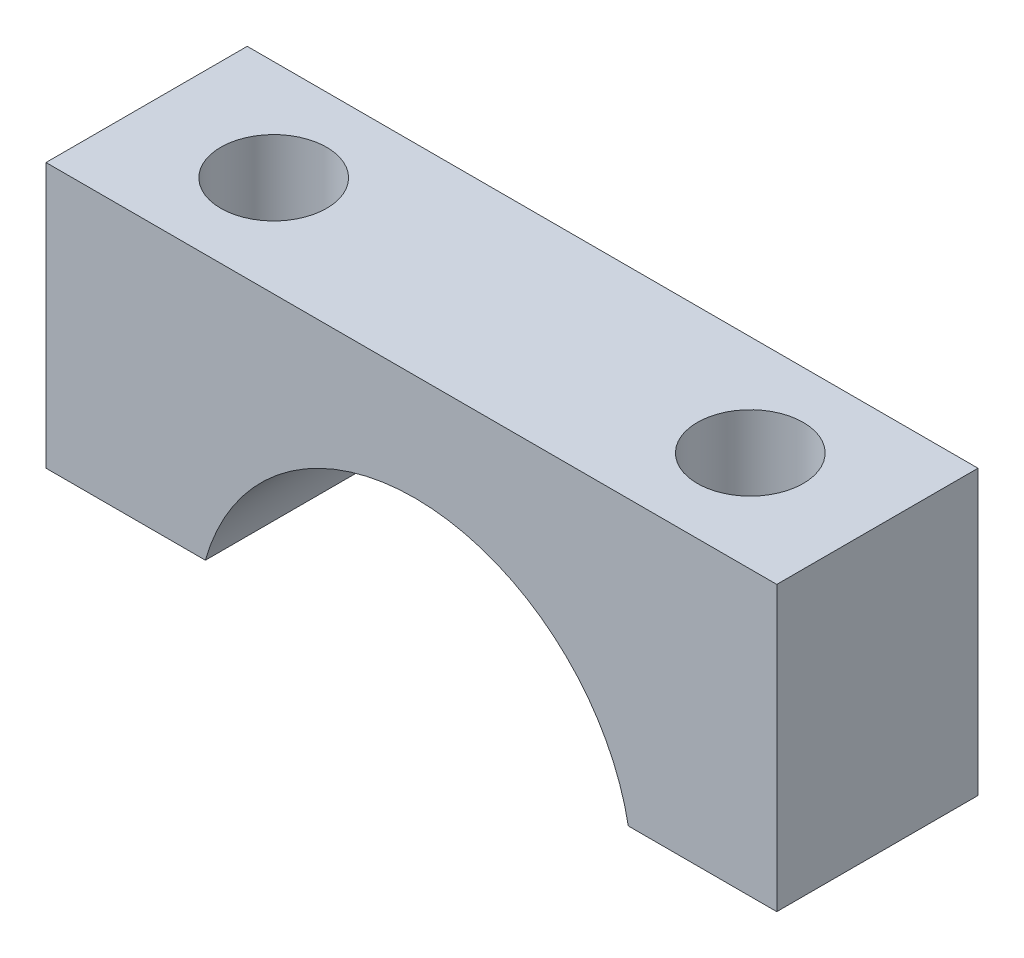
SolidWorks part; units mm, degrees
ref_plane "Front Plane" through (0, 0, 0) normal (0, 0, 1) x (1, 0, 0)
ref_plane "Top Plane" through (0, 0, 0) normal (0, 1, 0) x (1, 0, 0)
ref_plane "Right Plane" through (0, 0, 0) normal (1, 0, 0) x (0, 0, -1)
sketch "Sketch1" plane through (0, 0, 0) normal (0, 0, 1) x (1, 0, 0)
  line L3 (2476.9918, 1418.7932) -> (2476.9918, 1431.4932)
  line L4 (2476.9918, 1431.4932) -> (2512.0438, 1431.4932)
  line L5 (2512.0438, 1431.4932) -> (2512.0438, 1417.8978)
  line L6 (2476.9918, 1418.7932) -> (2484.6376, 1418.7932)
  line L7 (2512.0438, 1417.8978) -> (2504.9222, 1417.8978)
  arc A2 (2484.6376, 1418.7932) -> (2504.9222, 1417.8978) centre (2494.6754, 1415.9784) cw
  dimension "D1" = 12.7
extrude "Boss-Extrude1" add sketch "Sketch1" along normal blind 9.652
sketch "Sketch2" plane through (0, 1431.4932, 0) normal (0, 1, 0) x (1, 0, 0)
  line L0 (2476.9918, 0) -> (2476.9918, -9.652) construction
  line L1 (2512.0438, -9.652) -> (2476.9918, -9.652) construction
  line L2 (2476.9918, -9.652) -> (2476.9918, 0) construction
  line L3 (2494.5178, 3.619) -> (2494.5178, -13.8208) construction
  circle A0 centre (2483.0878, -4.826) radius 2.54
  circle A1 centre (2505.9478, -4.826) radius 2.54
  dimension "D1" = 11.43
  dimension "D2" = 11.43
extrude "Cut-Extrude1" cut sketch "Sketch2" against normal blind 5.08
